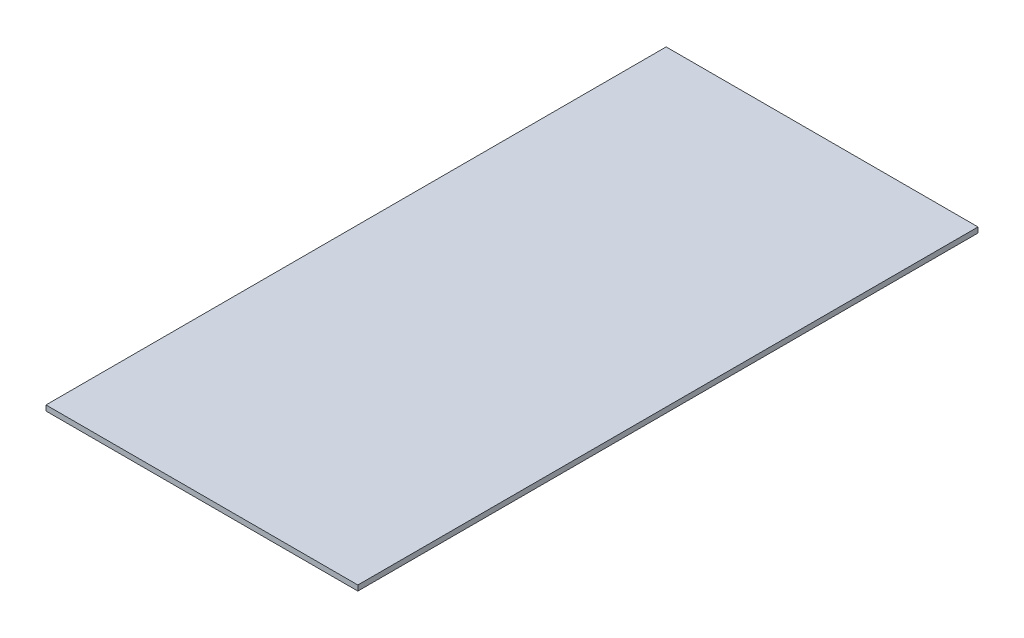
SolidWorks part; units mm, degrees
ref_plane "Front Plane" through (0, 0, 0) normal (0, 0, 1) x (1, 0, 0)
ref_plane "Top Plane" through (0, 0, 0) normal (0, 1, 0) x (1, 0, 0)
ref_plane "Right Plane" through (0, 0, 0) normal (1, 0, 0) x (0, 0, -1)
sketch "Sketch1" plane through (0, 0, 0) normal (0, 1, 0) x (1, 0, 0)
  line L1 (0, 0) -> (176, 0)
  line L2 (0, 0) -> (0, 350)
  line L3 (0, 350) -> (176, 350)
  line L4 (176, 0) -> (176, 350)
  dimension "D1" = 350
  dimension "D2" = 176
extrude "Boss-Extrude1" add sketch "Sketch1" along normal blind 3
